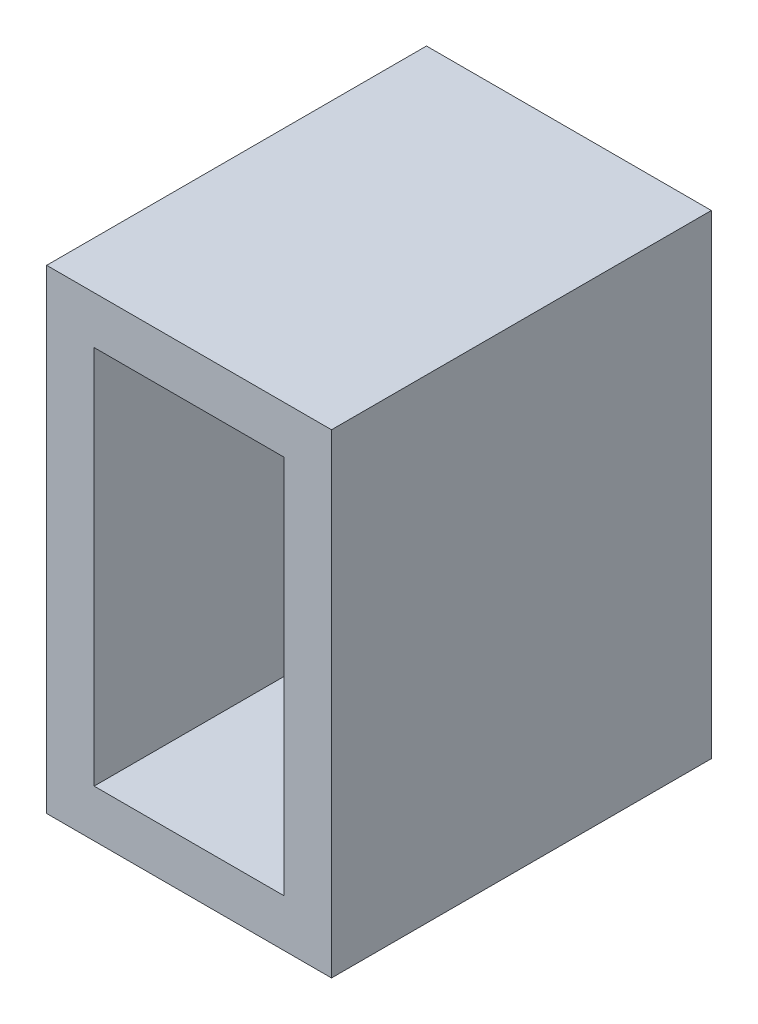
SolidWorks part; units mm, degrees
ref_plane "Front Plane" through (0, 0, 0) normal (0, 0, 1) x (1, 0, 0)
ref_plane "Top Plane" through (0, 0, 0) normal (0, 1, 0) x (1, 0, 0)
ref_plane "Right Plane" through (0, 0, 0) normal (1, 0, 0) x (0, 0, -1)
sketch "Sketch1" plane through (0, 0, 0) normal (0, 0, 1) x (1, 0, 0)
  line L0 (-8.5917, -2.2277) -> (-14.9417, -2.2277) construction
  line L1 (-14.9417, 29.5223) -> (23.1583, 29.5223)
  line L2 (-14.9417, 29.5223) -> (-14.9417, -33.9777)
  line L3 (-14.9417, -33.9777) -> (23.1583, -33.9777)
  line L4 (23.1583, 29.5223) -> (23.1583, -33.9777)
  line L5 (-8.5917, 23.1723) -> (16.8083, 23.1723)
  line L6 (-8.5917, 23.1723) -> (-8.5917, -27.6277)
  line L7 (-8.5917, -27.6277) -> (16.8083, -27.6277)
  line L8 (16.8083, 23.1723) -> (16.8083, -27.6277)
  line L9 (16.8083, 14.1585) -> (23.1583, 14.1585) construction
  line L10 (7.6819, 23.1723) -> (7.6819, 29.5223) construction
  line L11 (7.6819, -27.6277) -> (7.6819, -33.9777) construction
  dimension "D1" = 38.1
  dimension "D2" = 63.5
  dimension "D3" = 6.35
  dimension "D4" = 6.35
extrude "Boss-Extrude1" add sketch "Sketch1" along normal blind 50.8
ref_plane "Plane1" through (0, 0, 5.588) normal (0, 0, -1) x (-1, 0, 0)
ref_point "Point1"
ref_point "Point2"
sketch "Sketch4" plane through (0, 0, 5.588) normal (0, 0, -1) x (-1, 0, 0)
  line L0 (-4.1083, 17.7113) -> (-4.1083, 23.1723) construction
  line L1 (8.5917, 23.1723) -> (-16.8083, 23.1723) construction
  line L2 (8.5917, 23.1723) -> (8.5917, -27.6277) construction
  line L3 (8.5917, -27.6277) -> (-16.8083, -27.6277) construction
  line L4 (-16.8083, 23.1723) -> (-16.8083, -27.6277) construction
  line L5 (-16.8083, 23.1723) -> (8.5917, 23.1723)
  line L6 (-16.8083, 23.1723) -> (-16.8083, 17.7113)
  line L7 (-16.8083, 17.7113) -> (8.5917, 17.7113)
  line L8 (8.5917, 23.1723) -> (8.5917, 17.7113)
  line L9 (-16.8083, -27.6277) -> (8.5917, -27.6277)
  line L10 (-16.8083, -27.6277) -> (-16.8083, -22.1667)
  line L11 (-16.8083, -22.1667) -> (8.5917, -22.1667)
  line L12 (8.5917, -27.6277) -> (8.5917, -22.1667)
  line L13 (-4.1083, -22.1667) -> (-4.1083, -27.6277) construction
  line L14 (-13.8873, 17.7113) -> (-13.8873, -22.1667)
  line L15 (5.6707, -22.1667) -> (5.6707, 17.7113)
  line L16 (-13.8873, -2.2277) -> (-16.8083, -2.2277) construction
  line L17 (-13.8873, 17.7113) -> (-16.8083, 17.7113)
  line L18 (-13.8873, 17.7113) -> (-13.8873, -22.1667)
  line L19 (-13.8873, -22.1667) -> (-16.8083, -22.1667)
  line L20 (-16.8083, 17.7113) -> (-16.8083, -22.1667)
  line L21 (5.6707, -22.1667) -> (8.5917, -22.1667)
  line L22 (5.6707, -22.1667) -> (5.6707, 17.7113)
  line L23 (5.6707, 17.7113) -> (8.5917, 17.7113)
  line L24 (8.5917, -22.1667) -> (8.5917, 17.7113)
  line L25 (5.6707, -2.2277) -> (8.5917, -2.2277) construction
  dimension "D1" = 39.878
  dimension "D2" = 19.558
extrude "Boss-Extrude2" add sketch "Sketch4" against normal blind 2.54 contours L8 L5 L6 L7 | L7 L20 L11 L14 | L9 L12 L11 L10 | L11 L24 L7 L15
sketch "Sketch5" plane through (0, 0, 5.588) normal (0, 0, -1) x (-1, 0, 0)
  line L0 (-13.8873, -2.2277) -> (-16.8083, -2.2277) construction
  line L1 (-13.8873, 17.7113) -> (-13.8873, -22.1667) construction
  line L2 (-16.8083, 23.1723) -> (-16.8083, -27.6277) construction
  line L3 (5.6707, -2.2277) -> (8.5917, -2.2277) construction
  line L4 (5.6707, -22.1667) -> (5.6707, 17.7113) construction
  line L5 (8.5917, 23.1723) -> (8.5917, -27.6277) construction
  line L7 (-13.8873, -27.6277) -> (-16.8083, -27.6277)
  line L8 (-13.8873, -27.6277) -> (-13.8873, 23.1723)
  line L9 (-13.8873, 23.1723) -> (-16.8083, 23.1723)
  line L10 (-16.8083, -27.6277) -> (-16.8083, 23.1723)
  line L11 (-13.8873, -27.6277) -> (-16.8083, 23.1723) construction
  line L12 (-13.8873, 23.1723) -> (-16.8083, -27.6277) construction
  line L13 (5.6707, -27.6277) -> (8.5917, -27.6277)
  line L14 (5.6707, -27.6277) -> (5.6707, 23.1723)
  line L15 (5.6707, 23.1723) -> (8.5917, 23.1723)
  line L16 (8.5917, -27.6277) -> (8.5917, 23.1723)
  line L17 (5.6707, -27.6277) -> (8.5917, 23.1723) construction
  line L18 (5.6707, 23.1723) -> (8.5917, -27.6277) construction
  point P12 (-15.3478, -2.2277)
  point P18 (7.1312, -2.2277)
extrude "Boss-Extrude3" add sketch "Sketch5" along normal up to surface (5.588 mm away) up to face at (4.1083, -2.2277, 0)
sketch "Sketch6" plane through (0, 0, 5.588) normal (0, 0, -1) x (-1, 0, 0)
  line L0 (-13.8873, 20.4418) -> (5.6707, 20.4418) construction
  line L1 (-13.8873, 23.1723) -> (-13.8873, 17.7113) construction
  line L2 (5.6707, 23.1723) -> (5.6707, 17.7113) construction
  line L3 (-4.1083, 17.7113) -> (-4.1083, 23.1723) construction
  line L4 (-13.8873, 17.7113) -> (5.6707, 17.7113) construction
  line L5 (-13.8873, 23.1723) -> (5.6707, 23.1723) construction
  line L6 (-4.1083, -22.1667) -> (-4.1083, -27.6277) construction
  line L7 (-13.8873, -22.1667) -> (5.6707, -22.1667) construction
  line L8 (-13.8873, -27.6277) -> (5.6707, -27.6277) construction
  line L10 (-5.3783, 17.7113) -> (-2.8383, 17.7113)
  line L11 (-5.3783, 17.7113) -> (-5.3783, 23.1723)
  line L12 (-5.3783, 23.1723) -> (-2.8383, 23.1723)
  line L13 (-2.8383, 17.7113) -> (-2.8383, 23.1723)
  line L14 (-5.3783, 17.7113) -> (-2.8383, 23.1723) construction
  line L15 (-5.3783, 23.1723) -> (-2.8383, 17.7113) construction
  line L16 (-5.3783, -27.6277) -> (-2.8383, -27.6277)
  line L17 (-5.3783, -27.6277) -> (-5.3783, -22.1667)
  line L18 (-5.3783, -22.1667) -> (-2.8383, -22.1667)
  line L19 (-2.8383, -27.6277) -> (-2.8383, -22.1667)
  line L20 (-5.3783, -27.6277) -> (-2.8383, -22.1667) construction
  line L21 (-5.3783, -22.1667) -> (-2.8383, -27.6277) construction
  point P18 (-4.1083, 20.4418)
  point P23 (-4.1083, -24.8972)
  dimension "D1" = 2.54
  dimension "D2" = 2.54
extrude "Cut-Extrude1" cut sketch "Sketch6" against normal blind 2.54
